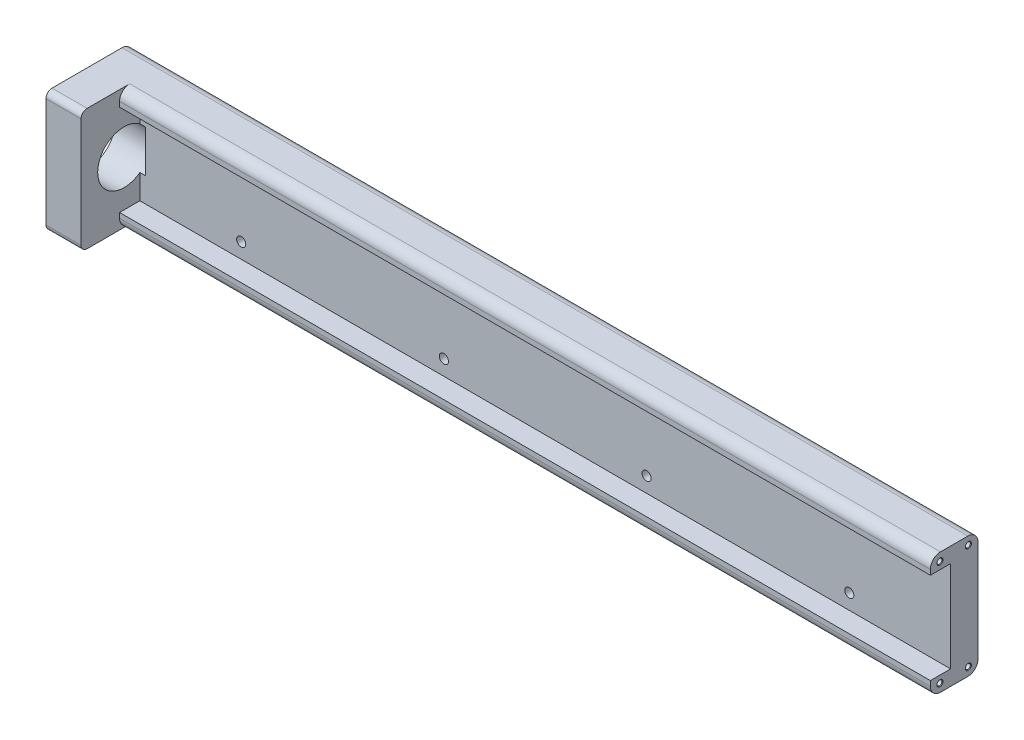
SolidWorks part; units mm, degrees
ref_plane "前视基准面" through (0, 0, 0) normal (0, 0, 1) x (1, 0, 0)
ref_plane "上视基准面" through (0, 0, 0) normal (0, 1, 0) x (1, 0, 0)
ref_plane "右视基准面" through (0, 0, 0) normal (1, 0, 0) x (0, 0, -1)
other "Configuration Table"
sketch "草图1" plane through (0, 0, 0) normal (0, 0, 1) x (1, 0, 0)
  line L1 (0, 0) -> (417.3, 0)
  line L2 (0, 0) -> (0, -60)
  line L3 (0, -60) -> (417.3, -60)
  line L4 (417.3, 0) -> (417.3, -60)
  dimension "D1" = 417.3
  dimension "D2" = 60
extrude "凸台-拉伸1" add sketch "草图1" along normal blind 23.5
sketch "草图2" plane through (0, 0, 23.5) normal (0, 0, 1) x (1, 0, 0)
  line L0 (417.3, 0) -> (0, 0) construction
  line L1 (17.3, -7.5) -> (417.3, -7.5)
  line L2 (17.3, -7.5) -> (17.3, -52.5)
  line L3 (17.3, -52.5) -> (417.3, -52.5)
  line L4 (417.3, -7.5) -> (417.3, -52.5)
  line L6 (417.3, -60) -> (417.3, 0) construction
  dimension "D1" = 400
  dimension "D2" = 45
  dimension "D3" = 7.5
extrude "切除-拉伸1" cut sketch "草图2" against normal blind 10
sketch "草图3" plane through (0, 0, 23.5) normal (0, 0, 1) x (1, 0, 0)
  line L0 (417.3, 0) -> (0, 0) construction
  line L1 (0, -60) -> (17.3, -60)
  line L2 (0, -60) -> (0, 0)
  line L3 (0, 0) -> (17.3, 0)
  line L4 (17.3, -60) -> (17.3, 0)
  line L5 (17.3, -7.5) -> (17.3, -52.5) construction
extrude "凸台-拉伸2" add sketch "草图3" along normal blind 19
hole_wizard "M3 螺纹孔1" positions "草图4" profile "草图5" tap size "M3" standard "GB"
sketch "草图4" plane through (417.3, 0, 0) normal (1, 0, 0) x (0, 0, -1)
  line L0 (-23.5, 0) -> (0, 0) construction
  line L1 (0, -60) -> (0, 0) construction
  point P0 (-4.75, -4)
  point P12 (-18.75, -4)
  point P13 (-18.75, -56)
  point P14 (-4.75, -56)
  dimension "D1" = 4
  dimension "D2" = 4.75
  dimension "D3" = 2
  dimension "D4" = 2
sketch "草图5" plane through (417.3, -4, 4.75) normal (0, 1, 0) x (0, 0, -1)
  line L0 (0, 0) -> (0, 8.2511)
  line L1 (0, 8.2511) -> (1.25, 7.5)
  line L2 (1.25, 7.5) -> (1.25, 0.275)
  line L3 (1.25, 0.275) -> (1.525, 0)
  line L5 (1.525, 0) -> (0, 0)
  line L6 (-1.25, 0.275) -> (-1.525, 0) construction
  line L10 (0, 8.2511) -> (-1.25, 7.5) construction
  line L11 (0, -6.35) -> (0, 107.95) construction
  dimension "螺纹孔钻头直径" = 2.5
  dimension "螺纹孔钻头深度" = 7.5
  dimension "近端锥形沉头孔直径" = 3.05
  dimension "近端锥形沉头孔角度" = 90
  dimension "导头角度" = 118
cosmetic thread "孔螺蚊线1" parameters "D1"=6, "D2"=3
cosmetic thread "孔螺蚊线2" parameters "D1"=6, "D2"=3
cosmetic thread "孔螺蚊线3" parameters "D1"=6, "D2"=3
cosmetic thread "孔螺蚊线4" parameters "D1"=6, "D2"=3
fillet "圆角1" radius 5 4 edges at (217.3, -60, 23.5) (208.65, -60, 0) (217.3, 0, 23.5) (208.65, 0, 0)
fillet "圆角2" radius 3 2 edges at (8.65, 0, 42.5) (8.65, -60, 42.5)
sketch "草图6" plane through (0, 0, 0) normal (-1, 0, 0) x (0, 0, 1)
  line L0 (0, -30) -> (42.5, -30) construction
  line L1 (0, -5) -> (0, -55) construction
  line L2 (42.5, -3) -> (42.5, -57) construction
  circle A0 centre (21.3, -30) radius 13
  dimension "D1" = 26
  dimension "D2" = 21.3
extrude "切除-拉伸2" cut sketch "草图6" against normal blind 20
hole_wizard "M4 螺纹孔1" positions "草图7" profile "草图8" tap size "M4" standard "GB"
sketch "草图7" plane through (0, 0, 0) normal (-1, 0, 0) x (0, 0, 1)
  line L0 (39.5, 0) -> (5, 0) construction
  line L1 (0, -5) -> (0, -55) construction
  point P0 (9.25, -11)
  point P11 (33.25, -11)
  point P12 (33.25, -49)
  point P13 (9.25, -49)
  dimension "D1" = 11
  dimension "D2" = 9.25
  dimension "D3" = 2
  dimension "D4" = 2
sketch "草图8" plane through (0, -11, 9.25) normal (0, 1, 0) x (0, 0, 1)
  line L0 (0, 0) -> (0, 11.0914)
  line L1 (0, 11.0914) -> (1.65, 10.1)
  line L2 (1.65, 10.1) -> (1.65, 0.375)
  line L3 (1.65, 0.375) -> (2.025, 0)
  line L5 (2.025, 0) -> (0, 0)
  line L6 (-1.65, 0.375) -> (-2.025, 0) construction
  line L10 (0, 11.0914) -> (-1.65, 10.1) construction
  line L11 (0, -6.35) -> (0, 107.95) construction
  dimension "螺纹孔钻头直径" = 3.3
  dimension "螺纹孔钻头深度" = 10.1
  dimension "近端锥形沉头孔直径" = 4.05
  dimension "近端锥形沉头孔角度" = 90
  dimension "导头角度" = 118
cosmetic thread "孔螺蚊线5" parameters "D1"=8, "D2"=4
cosmetic thread "孔螺蚊线6" parameters "D1"=8, "D2"=4
cosmetic thread "孔螺蚊线7" parameters "D1"=8, "D2"=4
cosmetic thread "孔螺蚊线8" parameters "D1"=8, "D2"=4
sketch "草图9" plane through (0, 0, 0) normal (0, 0, -1) x (-1, 0, 0)
  line L0 (-417.3, -55) -> (-417.3, -5) construction
  line L1 (-417.3, 0) -> (0, 0) construction
  circle A0 centre (-367.3, -15) radius 2.25
  circle A1 centre (-267.3, -15) radius 2.25
  circle A2 centre (-167.3, -15) radius 2.25
  circle A3 centre (-67.3, -15) radius 2.25
  circle A4 centre (-267.3, -45) radius 2.25
  circle A5 centre (-167.3, -45) radius 2.25
  circle A6 centre (-67.3, -45) radius 2.25
  circle A7 centre (-367.3, -45) radius 2.25
  dimension "D1" = 4.5
  dimension "D2" = 50
  dimension "D3" = 15
  dimension "D4" = 4
  dimension "D5" = 2
extrude "切除-拉伸3" cut sketch "草图9" against normal blind 15
